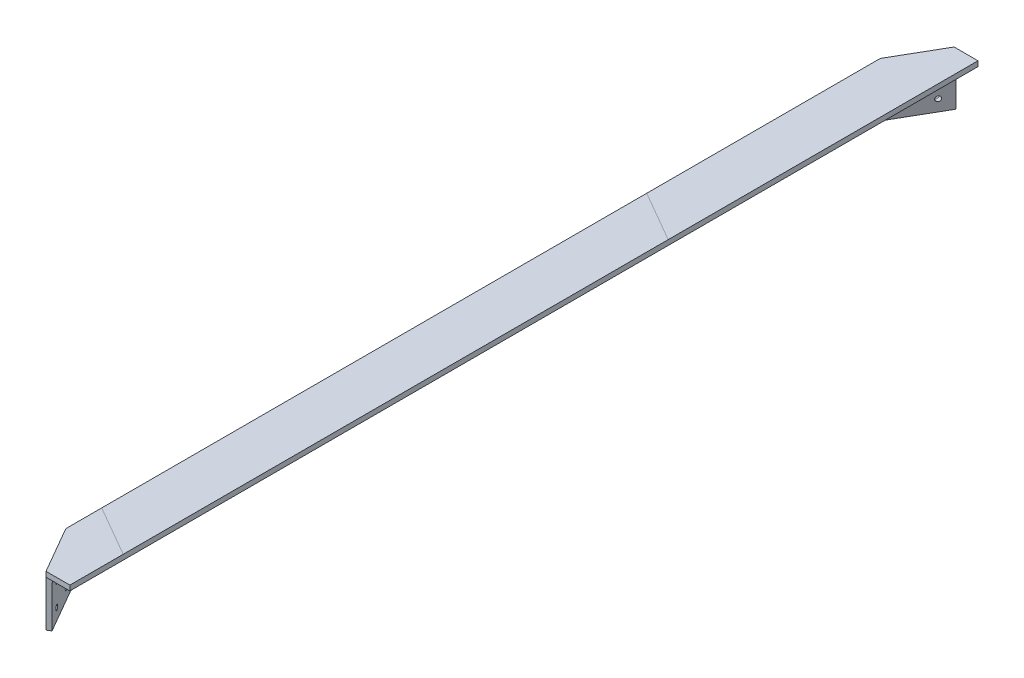
SolidWorks part; units mm, degrees
ref_plane "Front Plane" through (0, 0, 0) normal (0, 0, 1) x (1, 0, 0)
ref_plane "Top Plane" through (0, 0, 0) normal (0, 1, 0) x (1, 0, 0)
ref_plane "Right Plane" through (0, 0, 0) normal (1, 0, 0) x (0, 0, -1)
sketch "Sketch1" plane through (0, 0, 0) normal (0, 0, 1) x (1, 0, 0)
  line L0 (-8, 8) -> (72, 8)
  line L1 (72, 8) -> (72, 0)
  line L2 (72, 0) -> (0, 0)
  line L3 (0, 0) -> (0, -72)
  line L4 (0, -72) -> (-8, -72)
  line L5 (-8, -72) -> (-8, 8)
  dimension "D1" = 80
  dimension "D2" = 80
  dimension "D3" = 8
  dimension "D4" = 8
extrude "Boss-Extrude1" add sketch "Sketch1" along normal blind 640
sketch "Sketch3" plane through (0, 0, 0) normal (0, 1, 0) x (1, 0, 0)
  line L0 (-8, -640) -> (34.5, -713.6122)
  line L1 (34.5, -713.6122) -> (72, -713.6122)
  line L2 (72, -713.6122) -> (72, -640)
  line L3 (72, -640) -> (-8, -640)
  line L4 (-8, -640) -> (-8, 0) construction
  dimension "D1" = 210
  dimension "D2" = 85
extrude "Boss-Extrude2" add sketch "Sketch3" along normal blind 8
sketch "Sketch4" plane through (0, 0, 0) normal (0, -1, 0) x (1, 0, 0)
  line L0 (-8, 640) -> (34.5, 713.6122)
  line L1 (34.5, 713.6122) -> (40.5, 710.1481)
  line L2 (40.5, 710.1481) -> (0, 640)
  line L3 (-8, 640) -> (0, 640) construction
  line L4 (0, 640) -> (-8, 640)
  dimension "D1" = 8
extrude "Boss-Extrude3" add sketch "Sketch4" along normal blind 72
sketch "Sketch6" plane through (-277.1281, 0, 160) normal (0.866, 0, -0.5) x (-0.5, 0, -0.866)
  line L0 (-635.2563, -36) -> (-554.2563, -36) construction
  line L1 (-635.2563, -72) -> (-635.2563, 0) construction
  line L2 (-554.2563, -72) -> (-554.2563, 0) construction
  line L3 (-594.7563, 0) -> (-594.7563, -72) construction
  line L4 (-554.2563, 0) -> (-635.2563, 0) construction
  line L5 (-554.2563, -72) -> (-635.2563, -72) construction
  circle A0 centre (-615.0063, -18) radius 4
  circle A1 centre (-574.5063, -18) radius 4
  circle A2 centre (-574.5063, -54) radius 4
  circle A3 centre (-615.0063, -54) radius 4
  dimension "D1" = 20.25
  dimension "D3" = 8
  dimension "D2" = 18
extrude "Cut-Extrude1" cut sketch "Sketch6" against normal blind 8
fillet "Fillet1" radius 10 2 edges at (-8, -32, 640) (0, -36, 640)
fillet "Fillet2" radius 8 3 edges at (0, 0, 318.6603) (0.3407, 0, 639.9087) (20.9199, 0, 676.2343)
mirror "Mirror1" about plane through (0, 0, 0) normal (0, 0, 1) of "Boss-Extrude1", "Boss-Extrude2", "Boss-Extrude3", "Cut-Extrude1", "Fillet1", "Fillet2"
sketch "Sketch7" plane through (0, 8, 0) normal (0, 1, 0) x (1, 0, 0)
  line L0 (72, -629.7622) -> (-8, -583.5741)
  line L1 (72, -713.6122) -> (72, 713.6122) construction
  line L2 (-8, -637.3205) -> (-8, 637.3205) construction
  line L3 (-8, -583.5741) -> (-8, 272.9502)
  line L4 (-8, 272.9502) -> (72, 226.7622)
  line L5 (72, 226.7622) -> (72, -629.7622)
  dimension "D1" = 60
  dimension "D2" = 83.85
  dimension "D3" = 486.85
split line "Split Line1"
